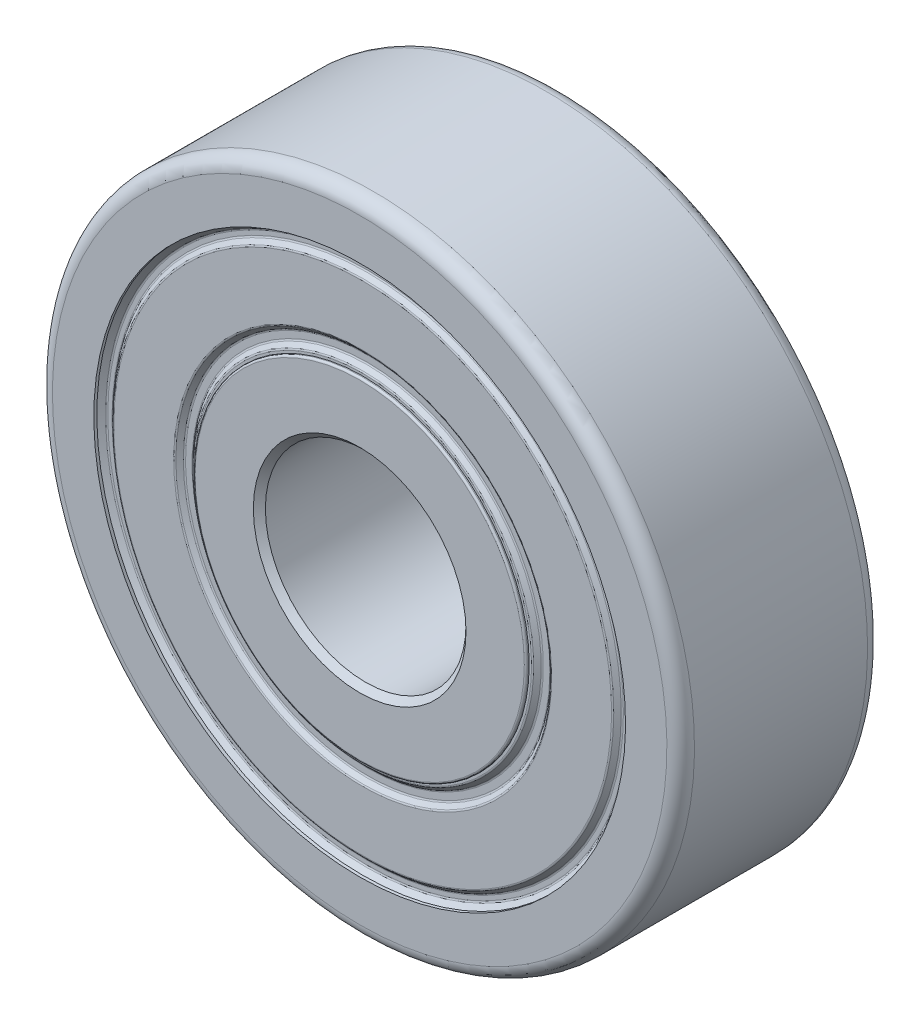
SolidWorks part; units mm, degrees
ref_plane "Front Plane" through (0, 0, 0) normal (0, 0, 1) x (1, 0, 0)
ref_plane "Top Plane" through (0, 0, 0) normal (0, 1, 0) x (1, 0, 0)
ref_plane "Right Plane" through (0, 0, 0) normal (1, 0, 0) x (0, 0, -1)
sketch "Sketch1" plane through (0, 0, 0) normal (0, 0, 1) x (1, 0, 0)
  line L0 (-8, 0) -> (-2.5, 0) construction
  line L1 (-2.5, 0) -> (2.5, 0) construction
  line L2 (2.5, 0) -> (8, 0) construction
  line L3 (0, 8) -> (0, 2.5) construction
  line L4 (0, 2.5) -> (0, 0) construction
  circle A0 centre (0, 0) radius 2.5 construction
  circle A1 centre (0, 0) radius 8 construction
  point P0 (0, 0)
  point P9 (0, 8)
  point P10 (0, 2.5)
  dimension "For Housing ID" = 16
  dimension "For Shaft Diameter" = 5
  dimension "OD" = 16
  dimension "ID" = 5
sketch "Sketch2" plane through (0, 0, 0) normal (1, 0, 0) x (0, 0, -1)
  line L1 (-2.5, -8) -> (2.5, -8) construction
  line L2 (-2.5, -8) -> (-2.5, 8) construction
  line L3 (-2.5, 8) -> (2.5, 8) construction
  line L4 (2.5, -8) -> (2.5, 8) construction
  line L5 (0, 8) -> (0, -8) construction
  line L6 (-2.5, 0) -> (2.5, 0) construction
  dimension "Width" = 5
sketch "Sketch3" plane through (0, 0, 0) normal (1, 0, 0) x (0, 0, -1)
  line L0 (-2.1562, 8) -> (2.5, 8) construction
  line L1 (-2.5, 2.5) -> (2.5, 2.5)
  line L2 (-2.5, -8) -> (-2.5, 8) construction
  line L3 (2.5, -8) -> (2.5, 8) construction
  line L4 (-2.5, 2.5) -> (-2.5, 4.15)
  line L5 (-2.5, 4.15) -> (2.5, 4.15) construction
  line L6 (2.5, 4.15) -> (2.5, 2.5)
  line L7 (-2.5, 8) -> (-2.5, 6.625) construction
  line L8 (-2.5, 6.625) -> (2.5, 6.625) construction
  line L9 (2.5, 6.625) -> (2.5, 8) construction
  line L10 (0, 6.625) -> (0, 4.15) construction
  line L11 (0, 6.9688) -> (0, 6.625) construction
  line L12 (0, 6.9688) -> (0, 7.3125) construction
  line L13 (0, 8) -> (0, 2.5) construction
  line L14 (0, 7.3125) -> (0, 7.6563) construction
  line L15 (0, 7.6563) -> (0, 8) construction
  line L21 (2.5, 6.625) -> (2.425, 6.625)
  line L22 (-2.5, 6.625) -> (-2.425, 6.625)
  line L23 (-2.1769, 6.6467) -> (-2.1025, 6.225)
  line L24 (-2.1025, 6.225) -> (-1.3412, 6.225)
  line L25 (1.3412, 6.225) -> (2.1025, 6.225)
  line L26 (2.1025, 6.225) -> (2.1769, 6.6467)
  line L27 (-2.5, 4.15) -> (-0.9844, 4.15)
  line L28 (2.5, 4.15) -> (0.9844, 4.15)
  line L29 (-2.1562, 8) -> (2.1562, 8)
  line L31 (2.5, 7.6562) -> (2.5, 6.625)
  line L33 (-2.5, 7.6562) -> (-2.5, 6.625)
  circle A0 centre (0, 5.3875) radius 1.5813 construction
  arc A3 (-2.425, 6.625) -> (-2.1769, 6.6467) centre (-2.3, 6.625) cw
  arc A4 (2.1769, 6.6467) -> (2.425, 6.625) centre (2.3, 6.625) cw
  arc A5 (-1.3412, 6.225) -> (1.3412, 6.225) centre (0, 5.3875) cw
  arc A8 (-0.9844, 4.15) -> (0.9844, 4.15) centre (0, 5.3875) ccw
  arc A9 (-2.1562, 8) -> (-2.5, 7.6562) centre (-2.1562, 7.6563) ccw
  arc A10 (2.5, 7.6562) -> (2.1562, 8) centre (2.1562, 7.6563) ccw
  dimension "D5" = 0.125
  dimension "REF" = 5.5
  dimension "D2" = 1.375
  dimension "D3" = 0.075
  dimension "D4" = 10
  dimension "D6" = 0.4
  dimension "D1" = 1.65
revolve "Revolve1" add sketch "Sketch3" angle 360 about L6
sketch "Sketch7" plane through (0, 0, 0) normal (0, 0, 1) x (1, 0, 0)
  line L0 (0, 8) -> (0, 0) construction
  line L1 (0, 3.8062) -> (0, 6.9688) construction
  line L2 (-1.5116, 4.9234) -> (0, 0) construction
  line L3 (0, 0) -> (1.5116, 4.9234) construction
  circle A0 centre (0, 5.3875) radius 1.5813 construction
  point P8 (0, 3.8062)
  dimension "Bearing Spacing" = 34.136
chamfer "Chamfer1" distance 0.15 angle 45 2 edges at (0, -2.5, -2.5) (0, -2.5, 2.5)
sketch "Sketch4" plane through (0, 0, 0) normal (1, 0, 0) x (0, 0, -1)
  line L3 (-2.1769, 6.6467) -> (-2.1769, 4.15)
  line L19 (-0.9844, 4.15) -> (-2.5, 4.15) construction
  line L23 (-2.1769, -6.6467) -> (-2.1769, 6.6467) construction
  line L25 (-2.1769, 4.15) -> (-2.3, 4.15)
  line L28 (-2.3, 6.625) -> (-2.3, 4.15) construction
  line L29 (-2.3, 4.15) -> (-2.3, 4.5625) construction
  line L34 (-2.3, 4.5625) -> (-2.425, 4.6875)
  line L37 (-2.425, -6.625) -> (-2.425, 6.625) construction
  line L39 (-2.425, 4.6875) -> (-2.425, 6.225)
  line L40 (-2.425, 6.225) -> (-2.3, 6.35)
  line L45 (-2.3, 6.35) -> (-2.3, 6.5)
  line L46 (-2.3, 6.5) -> (-2.425, 6.625)
  line L48 (-2.3, 4.3563) -> (-2.425, 4.2313)
  line L49 (-2.425, 4.2313) -> (-2.425, 4.15)
  line L50 (-2.425, 4.15) -> (-2.3, 4.15)
  line L51 (-2.3, 4.5625) -> (-2.3, 4.3563)
  arc A12 (-2.1769, 6.6467) -> (-2.425, 6.625) centre (-2.3, 6.625) ccw construction
  arc A13 (-2.1769, 6.6467) -> (-2.425, 6.625) centre (-2.3, 6.625) ccw
  dimension "D1" = 90
  dimension "D2" = 0.4125
  dimension "D3" = 0.275
revolve "Revolve2" add sketch "Sketch4" angle 360 about L6
fillet "Fillet2" radius 0.055 7 edges at (0, -4.2313, 2.425) (0, -4.3563, 2.3) (0, -4.5625, 2.3) (0, -4.6875, 2.425) (0, -6.225, 2.425) (0, -6.35, 2.3) (0, -6.5, 2.3)
sketch "Sketch5" plane through (0, 0, 0) normal (1, 0, 0) x (0, 0, -1)
  line L0 (0, 6.9688) -> (0, 3.8063)
  circle A0 centre (0, 5.3875) radius 1.5813 construction
  arc A1 (0, 3.8063) -> (0, 6.9688) centre (0, 5.3875) ccw
revolve "Revolve3" add sketch "Sketch5" angle 360 about L0
pattern_circular "CirPattern1" count 6 over 360 about axis through (0, 0, 0) along (0, 0, 1) of bodies 107
mirror "Mirror2" about plane through (0, 0, 0) normal (0, 0, 1) of bodies 106
fillet "Fillet3" radius 0.048 2 edges at (0, -4.15, -2.5) (0, -4.15, 2.5)
equation "\"D2@Sketch3\"=((\"OD@Sketch1\"-\"ID@Sketch1\")/2)*.25"
equation "\"D3@Sketch3\"=\"Width@Sketch2\"*.015"
equation "\"D5@Sketch3\"=\"Width@Sketch2\"*.025"
equation "\"D6@Sketch3\" = \"OD@Sketch1\" * .025"
equation "\"D1@Chamfer1\"=\"Width@Sketch2\"*.03"
equation "\"D1@CirPattern1\"=(360/\"Bearing Spacing@Sketch7\")-5"
equation "\"D2@Sketch4\"=((\"OD@Sketch1\"-\"ID@Sketch1\")/2)*.075"
equation "\"D3@Sketch4\"=((\"OD@Sketch1\"-\"ID@Sketch1\")/2)*.05"
equation "\"D1@Sketch3\"=((\"OD@Sketch1\"-\"ID@Sketch1\")/2)*.3"
equation "\"D1@Fillet2\"=((\"OD@Sketch1\"-\"ID@Sketch1\")/2)*.01"
equation "\"D1@Fillet3\"=\"OD@Sketch1\" * .003"
